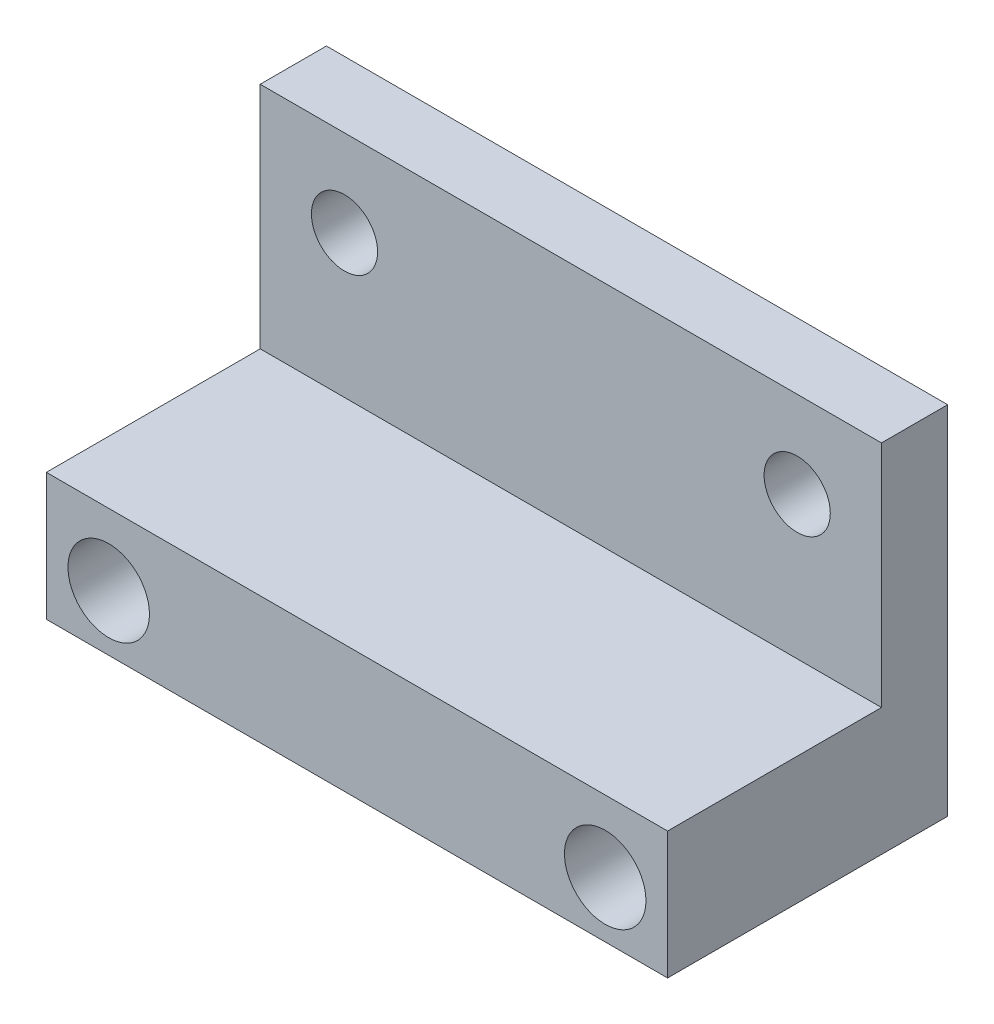
SolidWorks part; units mm, degrees
ref_plane "Front Plane" through (0, 0, 0) normal (0, 0, 1) x (1, 0, 0)
ref_plane "Top Plane" through (0, 0, 0) normal (0, 1, 0) x (1, 0, 0)
ref_plane "Right Plane" through (0, 0, 0) normal (1, 0, 0) x (0, 0, -1)
sketch "Sketch1" plane through (0, 0, 0) normal (0, 0, 1) x (1, 0, 0)
  line L1 (-12.2, 0) -> (12.2, 0)
  line L2 (-12.2, 0) -> (-12.2, 14)
  line L3 (-12.2, 14) -> (12.2, 14)
  line L4 (12.2, 0) -> (12.2, 14)
  circle A0 centre (-8.89, 10.6) radius 1.3
  circle A1 centre (8.89, 10.6) radius 1.3
  point P8 (0, 0)
  point P9 (0, 0)
  dimension "D3" = 2.6
  dimension "D1" = 14
  dimension "D2" = 24.4
  dimension "D4" = 8.89
  dimension "D5" = 8.89
  dimension "D6" = 10.6
  dimension "D7" = 17.78
extrude "Boss-Extrude1" add sketch "Sketch1" along normal blind 2.6
sketch "Sketch2" plane through (0, 0, 0) normal (0, 0, 1) x (1, 0, 0)
  line L0 (12.2, 0) -> (12.2, 14) construction
  line L1 (12.2, 5) -> (-12.2, 5)
  line L2 (12.2, 5) -> (12.2, 0)
  line L3 (12.2, 0) -> (-12.2, 0)
  line L4 (-12.2, 5) -> (-12.2, 0)
  dimension "D1" = 5
extrude "Boss-Extrude2" add sketch "Sketch2" along normal blind 11
sketch "Sketch3" plane through (0, 0, 11) normal (0, 0, 1) x (1, 0, 0)
  circle A0 centre (-9.75, 2.2) radius 1.6
  circle A1 centre (9.75, 2.2) radius 1.6
  point P4 (0, 0)
  dimension "D3" = 3.2
  dimension "D1" = 9.75
  dimension "D2" = 9.75
  dimension "D4" = 2.2
extrude "Cut-Extrude1" cut sketch "Sketch3" against normal blind 4.6
equation "\"D4@Sketch1\"=2.54*7/2"
